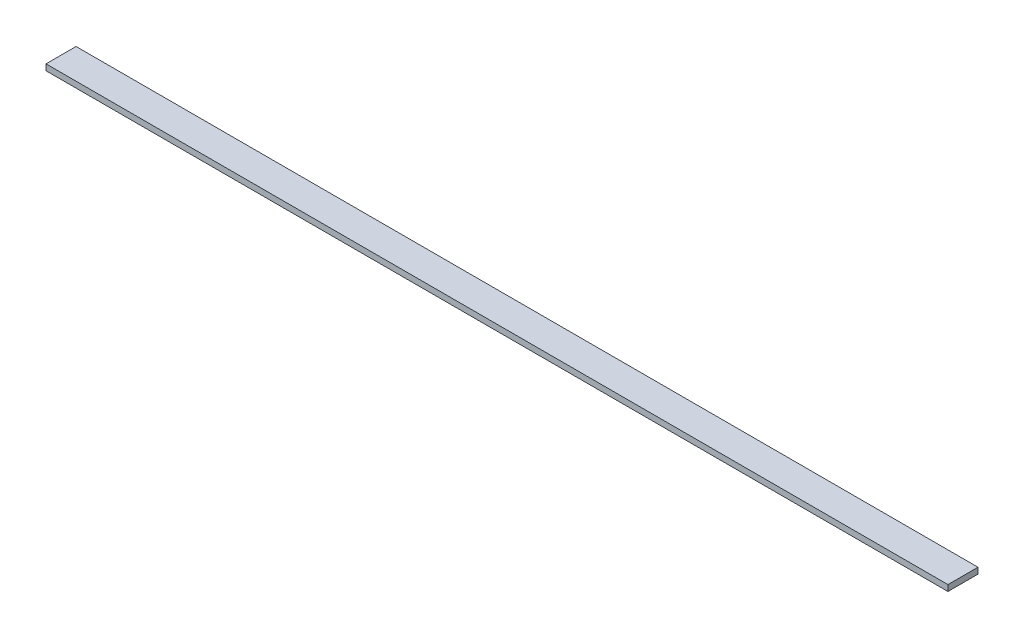
SolidWorks part; units mm, degrees
ref_plane "Plan de face" through (0, 0, 0) normal (0, 0, 1) x (1, 0, 0)
ref_plane "Plan de dessus" through (0, 0, 0) normal (0, 1, 0) x (1, 0, 0)
ref_plane "Plan de droite" through (0, 0, 0) normal (1, 0, 0) x (0, 0, -1)
sketch "Esquisse1" plane through (0, 0, 0) normal (0, 1, 0) x (1, 0, 0)
  line L1 (-300, -10) -> (300, -10)
  line L2 (-300, -10) -> (-300, 10)
  line L3 (-300, 10) -> (300, 10)
  line L4 (300, -10) -> (300, 10)
  line L5 (-300, -10) -> (300, 10) construction
  line L6 (-300, 10) -> (300, -10) construction
  point P0 (0, 0)
  dimension "D1" = 20
  dimension "D2" = 600
extrude "Boss.-Extru.1" add sketch "Esquisse1" along normal mid plane 4
